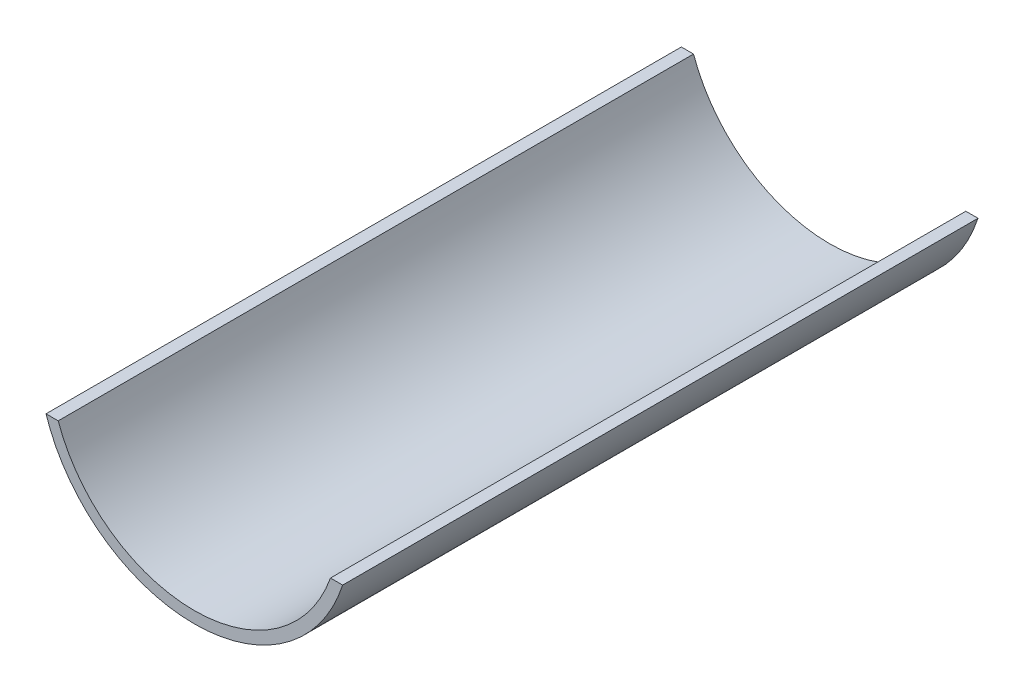
SolidWorks part; units mm, degrees
ref_plane "Front" through (0, 0, 0) normal (0, 0, 1) x (1, 0, 0)
ref_plane "Top" through (0, 0, 0) normal (0, 1, 0) x (1, 0, 0)
ref_plane "Right" through (0, 0, 0) normal (1, 0, 0) x (0, 0, -1)
sketch "Sketch1" plane through (0, 0, 0) normal (0, 0, 1) x (1, 0, 0)
  line L0 (77.0454, -25) -> (70.7107, -25)
  line L1 (-70.7107, -25) -> (-77.0454, -25)
  arc A0 (-70.7107, -25) -> (70.7107, -25) centre (0, 0) ccw
  arc A1 (-77.0454, -25) -> (77.0454, -25) centre (0, 0) ccw
  point P6 (-74.9485, -30.7201)
  dimension "D1" = 6
  dimension "D2" = 150
  dimension "D3" = 25
extrude "Boss-Extrude1" add sketch "Sketch1" along normal blind 330
